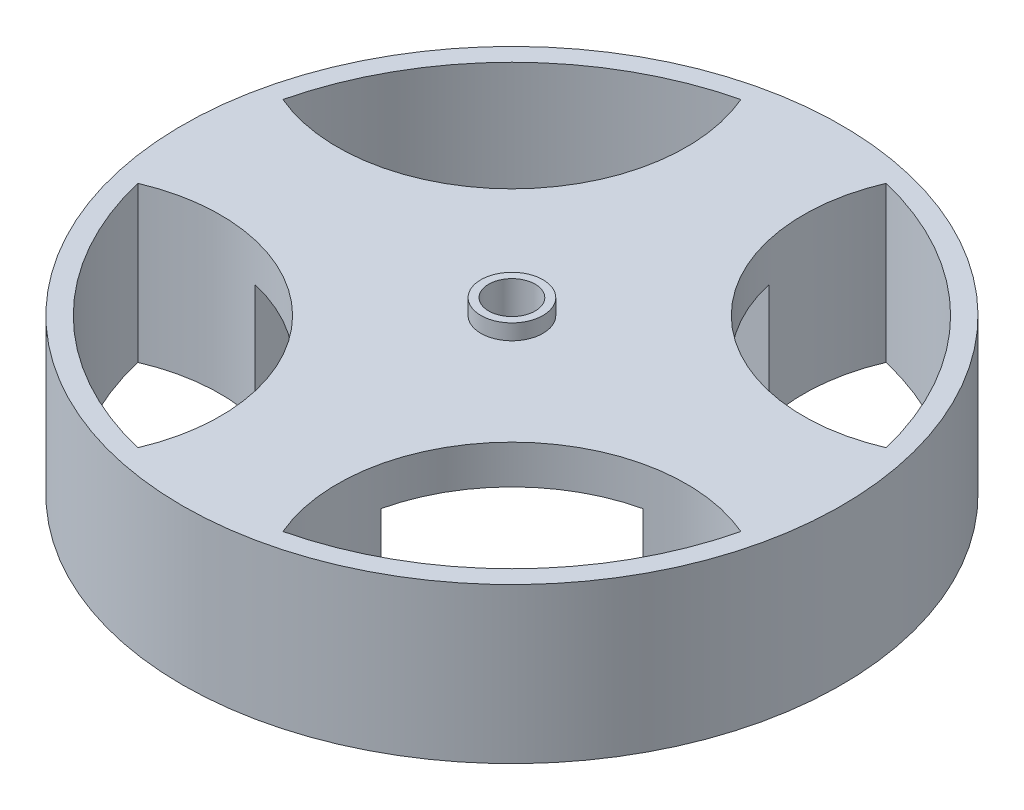
SolidWorks part; units mm, degrees
material "PLA"
ref_plane "Front Plane" through (0, 0, 0) normal (0, 0, 1) x (1, 0, 0)
ref_plane "Top Plane" through (0, 0, 0) normal (0, 1, 0) x (1, 0, 0)
ref_plane "Right Plane" through (0, 0, 0) normal (1, 0, 0) x (0, 0, -1)
sketch "Sketch1" plane through (0, 0, 0) normal (0, 1, 0) x (1, 0, 0)
  circle A0 centre (0, 0) radius 42.5
  circle A1 centre (0, 0) radius 40
  dimension "D1" = 85
  dimension "D2" = 80
extrude "Boss-Extrude1" add sketch "Sketch1" along normal mid plane 20
sketch "Sketch2" plane through (0, 10, 0) normal (0, 1, 0) x (1, 0, 0)
  line L0 (-42.5, 0) -> (42.5, 0) construction
  line L1 (0, 42.5) -> (0, -42.5) construction
  line L2 (-34.2667, -34.2667) -> (34.2667, 34.2667) construction
  line L3 (37.762, -37.762) -> (-37.762, 37.762) construction
  circle A0 centre (0, 0) radius 42.5 construction
  arc A1 (-38.8894, 9.3602) -> (-9.3602, 38.8894) centre (-30.052, 30.052) ccw
  arc A2 (9.3602, 38.8894) -> (38.8894, 9.3602) centre (30.052, 30.052) ccw
  arc A3 (38.8894, -9.3602) -> (9.3602, -38.8894) centre (30.052, -30.052) ccw
  arc A4 (-9.3602, -38.8894) -> (-38.8894, -9.3602) centre (-30.052, -30.052) ccw
  circle A5 centre (0, 0) radius 40 construction
  arc A6 (9.3602, 38.8894) -> (-9.3602, 38.8894) centre (0, 0) ccw
  arc A7 (-38.8894, 9.3602) -> (-38.8894, -9.3602) centre (0, 0) ccw
  arc A8 (-9.3602, -38.8894) -> (9.3602, -38.8894) centre (0, 0) ccw
  arc A9 (38.8894, -9.3602) -> (38.8894, 9.3602) centre (0, 0) ccw
  point P10 (0, 0)
  point P14 (0, 0)
  dimension "D3" = 45
  dimension "D1" = 45
  dimension "D2" = 45
extrude "Boss-Extrude2" add sketch "Sketch2" against normal blind 5
sketch "Sketch3" plane through (0, 10, 0) normal (0, 1, 0) x (1, 0, 0)
  circle A0 centre (0, 0) radius 4
  circle A1 centre (0, 0) radius 3
  dimension "D1" = 8
  dimension "D2" = 6
extrude "Boss-Extrude3" add sketch "Sketch3" along normal blind 2
sketch "Sketch4" plane through (0, 10, 0) normal (0, 1, 0) x (1, 0, 0)
  circle A0 centre (0, 0) radius 3
extrude "Cut-Extrude1" cut sketch "Sketch4" against normal through all
sketch "Sketch5" plane through (0, 5, 0) normal (0, -1, 0) x (1, 0, 0)
  line L0 (-40, 0) -> (-1.6862, 0) construction
  line L2 (-25, -8.1266) -> (-25, 8.1266)
  line L3 (-8.1266, 25) -> (8.1266, 25)
  line L4 (25, 8.1266) -> (25, -8.1266)
  line L5 (8.1266, -25) -> (-8.1266, -25)
  circle A0 centre (0, 0) radius 40 construction
  arc A4 (9.3602, 38.8894) -> (-9.3602, 38.8894) centre (0, 0) ccw
  arc A5 (-8.1266, 25) -> (-9.3602, 38.8894) centre (-30.052, 30.052) ccw
  arc A6 (9.3602, 38.8894) -> (8.1266, 25) centre (30.052, 30.052) ccw
  arc A7 (38.8894, -9.3602) -> (38.8894, 9.3602) centre (0, 0) ccw
  arc A8 (25, 8.1266) -> (38.8894, 9.3602) centre (30.052, 30.052) ccw
  arc A9 (38.8894, -9.3602) -> (25, -8.1266) centre (30.052, -30.052) ccw
  arc A10 (-9.3602, -38.8894) -> (9.3602, -38.8894) centre (0, 0) ccw
  arc A11 (8.1266, -25) -> (9.3602, -38.8894) centre (30.052, -30.052) ccw
  arc A12 (-38.8894, 9.3602) -> (-38.8894, -9.3602) centre (0, 0) ccw
  arc A13 (-9.3602, -38.8894) -> (-38.8894, -9.3602) centre (-30.052, -30.052) ccw
  arc A14 (-9.3602, -38.8894) -> (9.3602, -38.8894) centre (0, 0) ccw
  arc A15 (38.8894, -9.3602) -> (9.3602, -38.8894) centre (30.052, -30.052) ccw
  arc A16 (38.8894, -9.3602) -> (38.8894, 9.3602) centre (0, 0) ccw
  arc A17 (9.3602, 38.8894) -> (38.8894, 9.3602) centre (30.052, 30.052) ccw
  arc A18 (9.3602, 38.8894) -> (-9.3602, 38.8894) centre (0, 0) ccw
  arc A19 (-38.8894, 9.3602) -> (-9.3602, 38.8894) centre (-30.052, 30.052) ccw
  arc A20 (-38.8894, 9.3602) -> (-38.8894, -9.3602) centre (0, 0) ccw
  arc A21 (-25, -8.1266) -> (-38.8894, -9.3602) centre (-30.052, -30.052) ccw
  arc A27 (-38.8894, 9.3602) -> (-25, 8.1266) centre (-30.052, 30.052) ccw
  arc A28 (-9.3602, -38.8894) -> (-8.1266, -25) centre (-30.052, -30.052) ccw
  point P44 (0, 0)
  dimension "D1" = 0
  dimension "D2" = 25
  dimension "D3" = 4
extrude "Boss-Extrude4" add sketch "Sketch5" along normal blind 15
